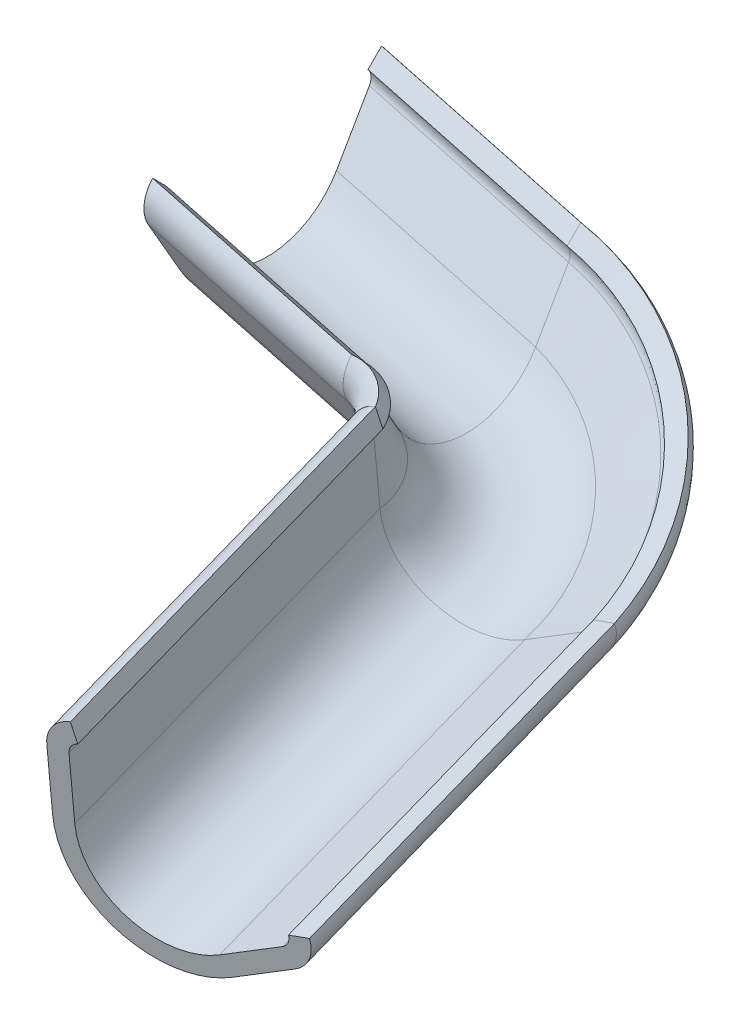
SolidWorks part; units mm, degrees
ref_plane "前基準面" through (0, 0, 0) normal (0, 0, 1) x (1, 0, 0)
ref_plane "上基準面" through (0, 0, 0) normal (0, 1, 0) x (1, 0, 0)
ref_plane "右基準面" through (0, 0, 0) normal (1, 0, 0) x (0, 0, -1)
sketch "草圖1" plane through (-6.0364, 0, 0) normal (1, 0, 0) x (0, 0, -1)
  line L0 (-14.5, 12.7962) -> (-14.5, 12.0212) construction
  line L1 (-29.5, 14.2869) -> (-14.9296, 13.0122) construction
  line L2 (-15.3936, 13.1497) -> (-15.2874, 13.0435)
  line L3 (-13.6064, 13.1497) -> (-13.7126, 13.0435)
  line L6 (-13.8288, 12.4087) -> (-13.572, 12.8535)
  line L8 (-13.9587, 12.4837) -> (-13.702, 12.9285)
  line L9 (-15.1712, 12.4087) -> (-15.428, 12.8535)
  line L10 (-15.0413, 12.4837) -> (-15.298, 12.9285)
  circle A0 centre (-14.5, 12.7962) radius 0.625 construction
  arc A1 (-13.6064, 13.1497) -> (-13.572, 12.8535) centre (-13.7886, 12.9785) cw
  arc A2 (-13.7126, 13.0435) -> (-13.702, 12.9285) centre (-13.7886, 12.9785) cw
  arc A8 (-15.0413, 12.4837) -> (-13.9587, 12.4837) centre (-14.5, 12.7962) ccw
  arc A9 (-15.1712, 12.4087) -> (-13.8288, 12.4087) centre (-14.5, 12.7962) ccw
  arc A10 (-15.2874, 13.0435) -> (-15.298, 12.9285) centre (-15.2114, 12.9785) ccw
  arc A11 (-15.3936, 13.1497) -> (-15.428, 12.8535) centre (-15.2114, 12.9785) ccw
  dimension "D1" = 0.15
  dimension "D4" = 0.1
  dimension "D5" = 0.3535
  dimension "D2" = 30
  dimension "D3" = 15
  dimension "D6" = 0.2473
ref_plane "平面1" through (0, 0, 14.5) normal (0, 0, -1) x (-1, 0, 0)
sketch3d "3D草圖3"
  line L0 (-6.0364, 12.7962, 14.5) -> (-4.4826, 12.3799, 14.4991)
  line L1 (-3.5941, 11.8555, 15.3398) -> (-3.514, 10.9959, 17.8014)
  line L5 (-6.0364, 12.7962, 14.5) -> (-6.0364, 12.0212, 14.5) construction
  arc A0 (-3.5941, 11.8555, 15.3398) -> (-4.4826, 12.3799, 14.4991) centre (-4.5629, 12.078, 15.4491) ccw
  point P15 (-3.6215, 12.1492, 14.4986)
  point P16 (-4.3169, 12.9956, 15.7615)
  dimension "D1" = 75
  dimension "D4" = 1
  dimension "D2" = 2.5
  dimension "D3" = 3.5
sweep "掃出1" add profiles "草圖1" path "3D草圖3"
